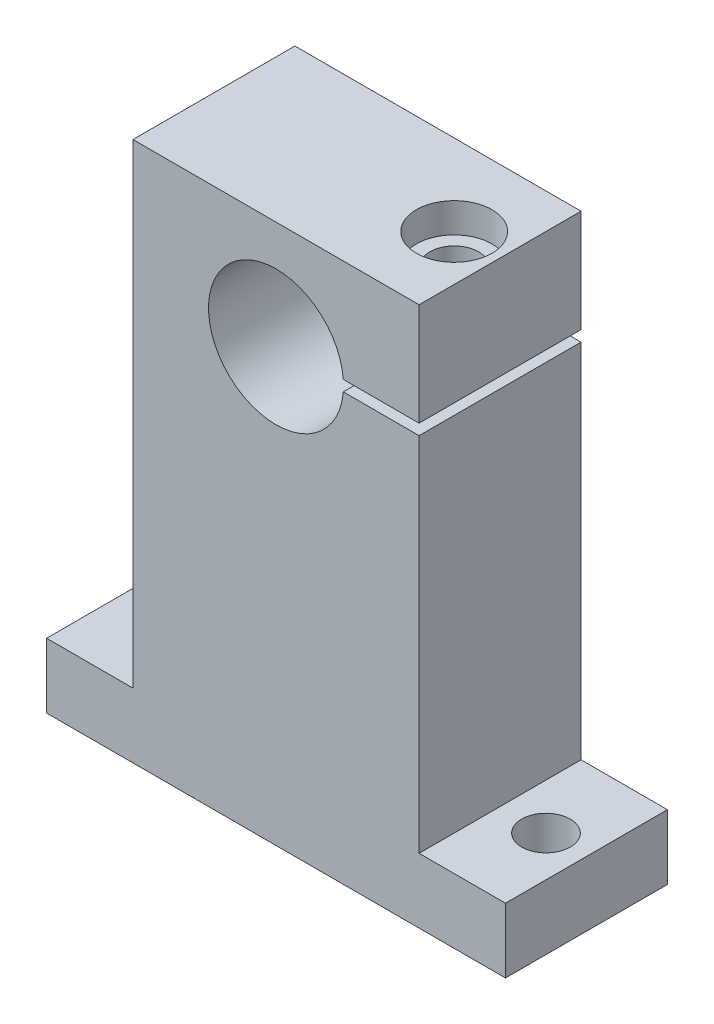
SolidWorks part; units mm, degrees
material "普通碳钢"
ref_plane "前视基准面" through (0, 0, 0) normal (0, 0, 1) x (1, 0, 0)
ref_plane "上视基准面" through (0, 0, 0) normal (0, 1, 0) x (1, 0, 0)
ref_plane "右视基准面" through (0, 0, 0) normal (1, 0, 0) x (0, 0, -1)
sketch "草图1" plane through (0, 0, 0) normal (0, 0, 1) x (1, 0, 0)
  line L0 (42.5, 0) -> (-42.5, 0)
  line L1 (-42.5, 0) -> (-42.5, 12)
  line L2 (-42.5, 12) -> (-26.5, 12)
  line L3 (-26.5, 12) -> (-26.5, 100)
  line L4 (-26.5, 100) -> (26.5, 100)
  line L5 (0, 100) -> (0, 0) construction
  line L6 (26.5, 12) -> (26.5, 100)
  line L7 (42.5, 12) -> (26.5, 12)
  line L8 (42.5, 0) -> (42.5, 12)
  circle A0 centre (0, 80) radius 12.5
  dimension "D5" = 25
  dimension "D6" = 80
  dimension "D1" = 53
  dimension "D2" = 12
  dimension "D3" = 100
  dimension "D4" = 85
extrude "凸台-拉伸1" add sketch "草图1" along normal mid plane 30
hole_wizard "孔1" positions "草图3" profile "草图2" legacy
sketch "草图3" plane through (0, 0, 0) normal (0, -1, 0) x (1, 0, 0)
  line L0 (0, -15) -> (0, 15) construction
  line L1 (-42.5, -15) -> (42.5, -15) construction
  line L2 (-42.5, 15) -> (42.5, 15) construction
  point P0 (-35, 0)
  point P1 (35, 0)
  dimension "D1" = 70
sketch "草图2" plane through (-35, 0, 0) normal (1, 0, 0) x (0, 0, -1)
  line L0 (0, 0) -> (0, 100)
  line L1 (0, 100) -> (4.5, 100)
  line L2 (4.5, 100) -> (4.5, 0)
  line L3 (4.5, 0) -> (0, 0)
  line L4 (0, 110) -> (0, -10) construction
  dimension "直径" = 9
  dimension "深度" = 100
sketch "草图4" plane through (0, 0, 15) normal (0, 0, 1) x (1, 0, 0)
  line L0 (0, 80) -> (88.4511, 80) construction
  line L1 (60.3456, 79) -> (6.9989, 79)
  line L2 (60.3456, 79) -> (60.3456, 81)
  line L3 (60.3456, 81) -> (6.9989, 81)
  line L4 (6.9989, 79) -> (6.9989, 81)
  line L5 (60.3456, 79) -> (6.9989, 81) construction
  line L6 (60.3456, 81) -> (6.9989, 79) construction
  dimension "D1" = 2
extrude "切除-拉伸1" cut sketch "草图4" against normal through all
hole_wizard "M8 六角头螺钉的柱形沉头孔1" positions "草图6" profile "草图7" counterbore size "M8" standard "Ansi Metric"
sketch "草图6" plane through (-72.6995, 100, 2.2819) normal (0, -1, 0) x (0, 0, -1)
  line L0 (-12.7181, 99.1995) -> (17.2819, 99.1995) construction
  line L1 (2.2819, 99.1995) -> (2.2819, 46.1995) construction
  line L2 (-12.7181, 46.1995) -> (17.2819, 46.1995) construction
  line L4 (-12.7181, 72.6995) -> (17.2819, 72.6995) construction
  line L5 (-12.7181, 99.1995) -> (-12.7181, 46.1995) construction
  line L6 (17.2819, 99.1995) -> (17.2819, 46.1995) construction
  point P0 (2.2819, 90.6995)
  dimension "D1" = 18
sketch "草图7" plane through (18, 100, 0) normal (1, 0, 0) x (0, 0, 1)
  line L0 (0, 0) -> (0, 37.5537)
  line L1 (0, 37.5537) -> (4.25, 35)
  line L2 (4.25, 35) -> (4.25, 5.5)
  line L3 (4.25, 5.5) -> (7, 5.5)
  line L4 (7, 5.5) -> (7, 0)
  line L5 (7, 0) -> (0, 0)
  line L10 (0, 37.5537) -> (-4.25, 35) construction
  line L11 (0, -6.35) -> (0, 107.95) construction
  dimension "孔直径" = 8.5
  dimension "孔深度" = 35
  dimension "柱形沉头孔直径" = 14
  dimension "柱形沉头孔深度" = 5.5
  dimension "导头角度" = 118
sketch "草图8" plane through (0, 94.5, 0) normal (0, 1, 0) x (1, 0, 0)
  circle A0 centre (18, 0) radius 4.5
  dimension "D1" = 9
extrude "切除-拉伸2" cut sketch "草图8" against normal up to next
